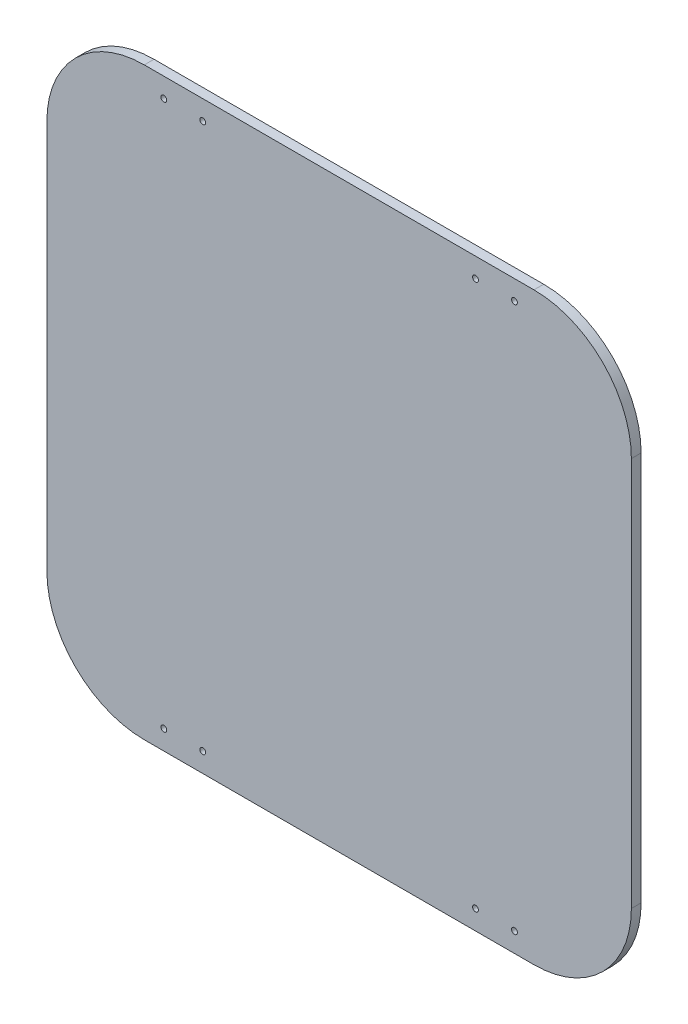
SolidWorks part; units mm, degrees
ref_plane "Front Plane" through (0, 0, 0) normal (0, 0, 1) x (1, 0, 0)
ref_plane "Top Plane" through (0, 0, 0) normal (0, 1, 0) x (1, 0, 0)
ref_plane "Right Plane" through (0, 0, 0) normal (1, 0, 0) x (0, 0, -1)
sketch "Sketch1" plane through (0, 0, 0) normal (0, 0, 1) x (1, 0, 0)
  line L8 (-100, -150) -> (100, -150)
  line L9 (150, -100) -> (150, 100)
  line L10 (100, 150) -> (-100, 150)
  line L11 (-150, 100) -> (-150, -100)
  circle A4 centre (-70, 140) radius 1.5
  circle A5 centre (-90, 140) radius 1.5
  circle A7 centre (70, 140) radius 1.5
  circle A13 centre (90, -140) radius 1.5
  circle A14 centre (70, -140) radius 1.5
  circle A15 centre (-70, -140) radius 1.5
  circle A16 centre (-90, -140) radius 1.5
  circle A17 centre (90, 140) radius 1.5
  arc A26 (100, -150) -> (150, -100) centre (100, -100) ccw
  arc A27 (150, 100) -> (100, 150) centre (100, 100) ccw
  arc A28 (-100, 150) -> (-150, 100) centre (-100, 100) ccw
  arc A29 (-150, -100) -> (-100, -150) centre (-100, -100) ccw
extrude "Boss-Extrude1" add sketch "Sketch1" along normal blind 5
